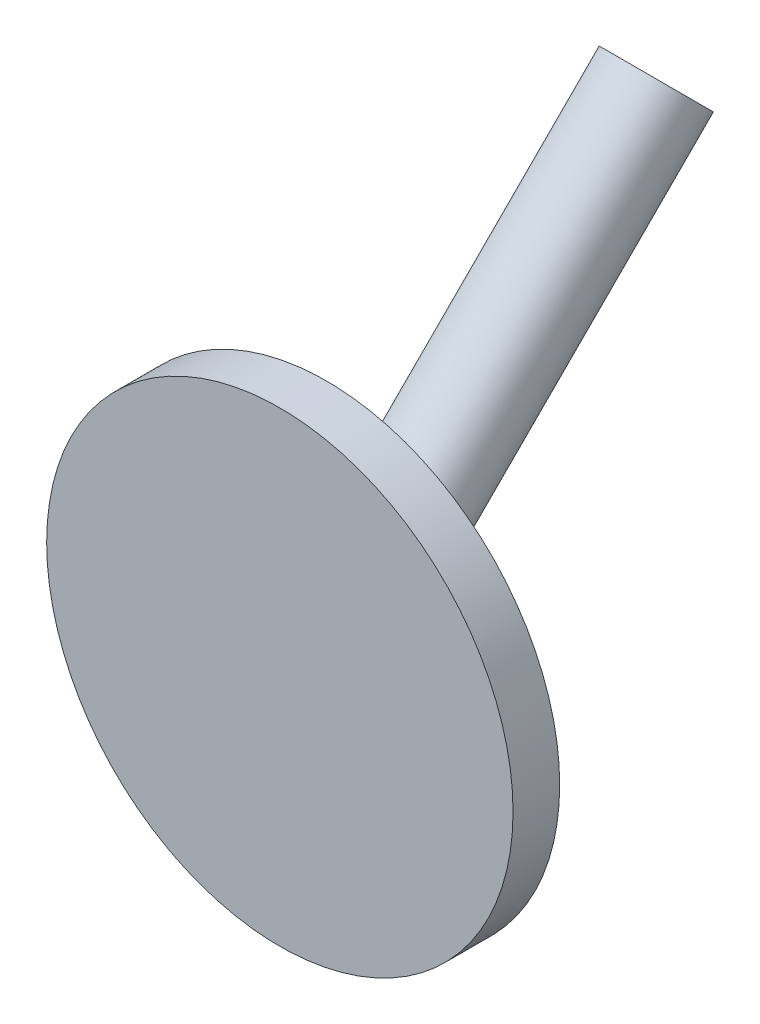
SolidWorks part; units mm, degrees
material "Glass"
ref_plane "Front Plane" through (0, 0, 0) normal (0, 0, 1) x (1, 0, 0)
ref_plane "Top Plane" through (0, 0, 0) normal (0, 1, 0) x (1, 0, 0)
ref_plane "Right Plane" through (0, 0, 0) normal (1, 0, 0) x (0, 0, -1)
sketch "Sketch1" plane through (0, 0, 0) normal (0, 0, 1) x (1, 0, 0)
  circle A0 centre (0, 0) radius 10
  dimension "D1" = 20
extrude "Boss-Extrude1" add sketch "Sketch1" along normal blind 2
sketch "Sketch2" plane through (0, 0, 0) normal (1, 0, 0) x (0, 0, -1)
  line L0 (0, 0) -> (45.2676, 45.2676) construction
  line L1 (0, 0) -> (13.6656, 0) construction
  line L2 (0, 0) -> (76.3646, -76.3646) construction
  point P3 (76.3646, -76.3646)
  point P6 (45.2676, 45.2676)
  point P7 (0, 0)
  dimension "D1" = 45
  dimension "D2" = 45
ref_plane "Plane1" through (0, 0, 0) normal (0, 0.7071, -0.7071) x (-1, 0, 0)
ref_plane "Plane2" through (0, 0, 0) normal (0, -0.7071, -0.7071) x (-1, 0, 0)
sketch "Sketch3" plane through (0, 0, 0) normal (0, -0.7071, -0.7071) x (-1, 0, 0)
  circle A0 centre (0, 0) radius 2
  dimension "D1" = 4
extrude "Boss-Extrude2" add sketch "Sketch3" along normal blind 10
sketch "Sketch4" plane through (0, 0, 0) normal (0, 0.7071, -0.7071) x (-1, 0, 0)
  circle A0 centre (0, 0) radius 2
  dimension "D1" = 4
extrude "Boss-Extrude3" add sketch "Sketch4" along normal blind 20
